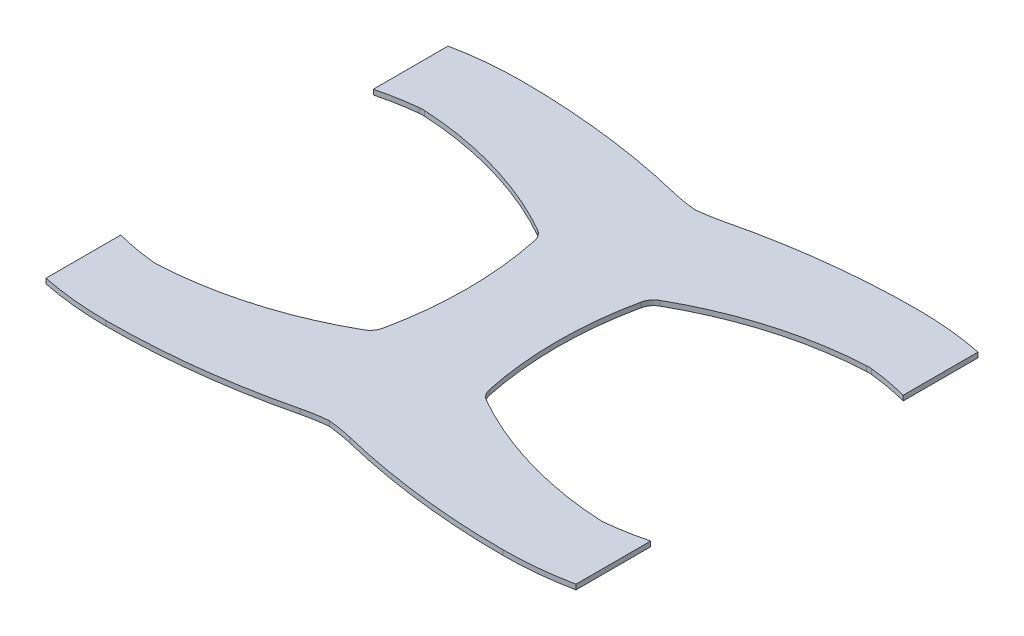
SolidWorks part; units mm, degrees
ref_plane "Front Plane" through (0, 0, 0) normal (0, 0, 1) x (1, 0, 0)
ref_plane "Top Plane" through (0, 0, 0) normal (0, 1, 0) x (1, 0, 0)
ref_plane "Right Plane" through (0, 0, 0) normal (1, 0, 0) x (0, 0, -1)
sketch "Sketch1" plane through (0, 0, 0) normal (0, 1, 0) x (1, 0, 0)
  line L0 (0, 246) -> (0, 201) construction
  line L1 (319, 246) -> (319, 201) construction
  line L2 (0, 49) -> (0, 4) construction
  line L3 (319, 49) -> (319, 4) construction
  line L4 (319, 246) -> (319, 201)
  line L5 (319, 49) -> (319, 4)
  line L6 (0, 49) -> (0, 4)
  line L7 (0, 246) -> (0, 201)
  arc A0 (319, 201) -> (295.6164, 205.267) centre (279, 48) ccw construction
  arc A1 (122.6108, 177.2489) -> (26.5903, 205.3471) centre (14.4322, -14.3167) ccw construction
  arc A2 (127.4763, 79.3852) -> (127.4763, 170.6148) centre (-87.7429, 125) ccw construction
  arc A3 (127.4763, 170.6148) -> (122.6108, 177.2489) centre (117.6936, 168.5414) ccw construction
  arc A4 (26.5903, 205.3471) -> (23.3836, 205.267) centre (25.485, 185.3777) ccw construction
  arc A5 (23.3836, 205.267) -> (0, 201) centre (40, 48) ccw construction
  arc A6 (144.5, 237.5) -> (40, 250) centre (40, -193.06) ccw construction
  arc A7 (40, 250) -> (0, 246) centre (40, 48) ccw construction
  arc A8 (144.5, 237.5) -> (159.5, 235) centre (169.1036, 338.8714) ccw construction
  arc A9 (159.5, 235) -> (174.5, 237.5) centre (149.8964, 338.8714) ccw construction
  arc A10 (279, 250) -> (174.5, 237.5) centre (279, -193.06) ccw construction
  arc A11 (319, 246) -> (279, 250) centre (279, 48) ccw construction
  arc A12 (295.6164, 205.267) -> (292.4097, 205.3471) centre (293.515, 185.3777) ccw construction
  arc A13 (292.4097, 205.3471) -> (196.3892, 177.2489) centre (304.5678, -14.3167) ccw construction
  arc A14 (196.3892, 177.2489) -> (191.5237, 170.6148) centre (201.3064, 168.5414) ccw construction
  arc A15 (191.5237, 170.6148) -> (191.5237, 79.3852) centre (406.7429, 125) ccw construction
  arc A16 (122.6108, 72.7511) -> (127.4763, 79.3852) centre (117.6936, 81.4586) ccw construction
  arc A17 (26.5903, 44.6529) -> (122.6108, 72.7511) centre (14.4322, 264.3167) ccw construction
  arc A18 (23.3836, 44.733) -> (26.5903, 44.6529) centre (25.485, 64.6223) ccw construction
  arc A19 (0, 49) -> (23.3836, 44.733) centre (40, 202) ccw construction
  arc A20 (40, 0) -> (144.5, 12.5) centre (40, 443.06) ccw construction
  arc A21 (0, 4) -> (40, 0) centre (40, 202) ccw construction
  arc A22 (159.5, 15) -> (144.5, 12.5) centre (169.1036, -88.8714) ccw construction
  arc A23 (174.5, 12.5) -> (159.5, 15) centre (149.8964, -88.8714) ccw construction
  arc A24 (174.5, 12.5) -> (279, 0) centre (279, 443.06) ccw construction
  arc A25 (279, 0) -> (319, 4) centre (279, 202) ccw construction
  arc A26 (295.6164, 44.733) -> (319, 49) centre (279, 202) ccw construction
  arc A27 (196.3892, 72.7511) -> (292.4097, 44.6529) centre (304.5678, 264.3167) ccw construction
  arc A28 (292.4097, 44.6529) -> (295.6164, 44.733) centre (293.515, 64.6223) ccw construction
  arc A29 (191.5237, 79.3852) -> (196.3892, 72.7511) centre (201.3064, 81.4586) ccw construction
  arc A30 (144.5, 237.5) -> (159.5, 235) centre (169.1036, 338.8714) ccw
  arc A31 (159.5, 235) -> (174.5, 237.5) centre (149.8964, 338.8714) ccw
  arc A32 (279, 250) -> (174.5, 237.5) centre (279, -193.06) ccw
  arc A33 (319, 246) -> (279, 250) centre (279, 48) ccw
  arc A34 (295.6164, 205.267) -> (292.4097, 205.3471) centre (293.515, 185.3777) ccw
  arc A35 (319, 201) -> (295.6164, 205.267) centre (279, 48) ccw
  arc A36 (292.4097, 205.3471) -> (196.3892, 177.2489) centre (304.5678, -14.3167) ccw
  arc A37 (196.3892, 177.2489) -> (191.5237, 170.6148) centre (201.3064, 168.5414) ccw
  arc A38 (191.5237, 79.3852) -> (196.3892, 72.7511) centre (201.3064, 81.4586) ccw
  arc A39 (191.5237, 170.6148) -> (191.5237, 79.3852) centre (406.7429, 125) ccw
  arc A40 (196.3892, 72.7511) -> (292.4097, 44.6529) centre (304.5678, 264.3167) ccw
  arc A41 (292.4097, 44.6529) -> (295.6164, 44.733) centre (293.515, 64.6223) ccw
  arc A42 (295.6164, 44.733) -> (319, 49) centre (279, 202) ccw
  arc A43 (279, 0) -> (319, 4) centre (279, 202) ccw
  arc A44 (174.5, 12.5) -> (279, 0) centre (279, 443.06) ccw
  arc A45 (174.5, 12.5) -> (159.5, 15) centre (149.8964, -88.8714) ccw
  arc A46 (159.5, 15) -> (144.5, 12.5) centre (169.1036, -88.8714) ccw
  arc A47 (0, 4) -> (40, 0) centre (40, 202) ccw
  arc A48 (40, 0) -> (144.5, 12.5) centre (40, 443.06) ccw
  arc A49 (23.3836, 44.733) -> (26.5903, 44.6529) centre (25.485, 64.6223) ccw
  arc A50 (0, 49) -> (23.3836, 44.733) centre (40, 202) ccw
  arc A51 (26.5903, 44.6529) -> (122.6108, 72.7511) centre (14.4322, 264.3167) ccw
  arc A52 (122.6108, 72.7511) -> (127.4763, 79.3852) centre (117.6936, 81.4586) ccw
  arc A53 (127.4763, 79.3852) -> (127.4763, 170.6148) centre (-87.7429, 125) ccw
  arc A54 (127.4763, 170.6148) -> (122.6108, 177.2489) centre (117.6936, 168.5414) ccw
  arc A55 (26.5903, 205.3471) -> (23.3836, 205.267) centre (25.485, 185.3777) ccw
  arc A56 (122.6108, 177.2489) -> (26.5903, 205.3471) centre (14.4322, -14.3167) ccw
  arc A57 (23.3836, 205.267) -> (0, 201) centre (40, 48) ccw
  arc A58 (40, 250) -> (0, 246) centre (40, 48) ccw
  arc A59 (144.5, 237.5) -> (40, 250) centre (40, -193.06) ccw
extrude "Boss-Extrude1" add sketch "Sketch1" against normal blind 3 from offset 10
